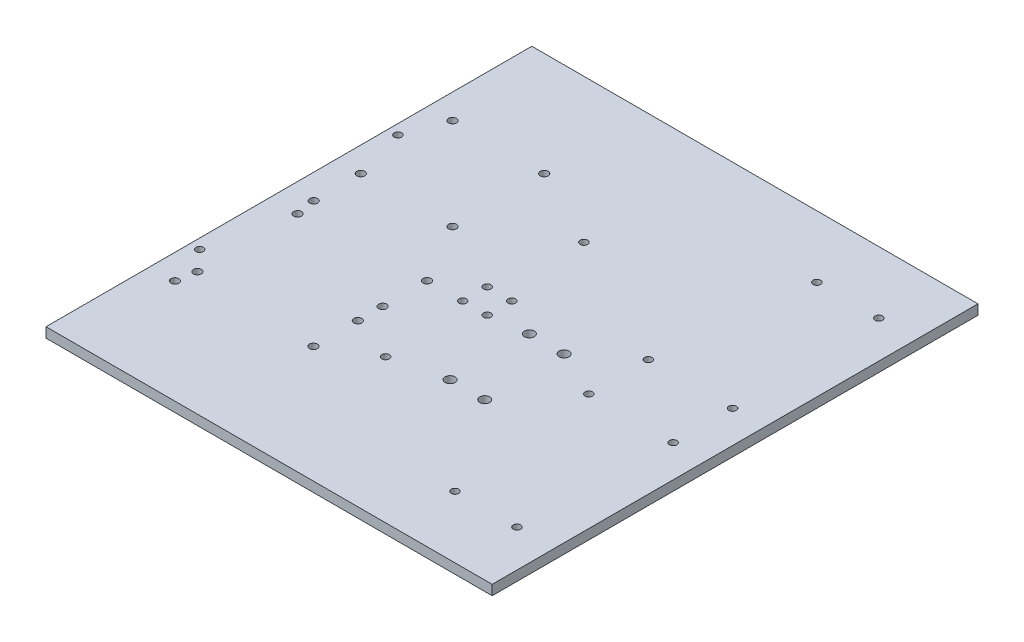
SolidWorks part; units mm, degrees
ref_plane "前视基准面" through (0, 0, 0) normal (0, 0, 1) x (1, 0, 0)
ref_plane "上视基准面" through (0, 0, 0) normal (0, 1, 0) x (1, 0, 0)
ref_plane "右视基准面" through (0, 0, 0) normal (1, 0, 0) x (0, 0, -1)
other "Configuration Table"
sketch "草图1" plane through (0, 0, 0) normal (0, 1, 0) x (1, 0, 0)
  line L1 (-90, -80) -> (90, -80)
  line L2 (-90, -80) -> (-90, 80)
  line L3 (-90, 80) -> (90, 80)
  line L4 (90, -80) -> (90, 80)
  line L5 (-90, -80) -> (90, 80) construction
  line L6 (-90, 80) -> (90, -80) construction
  point P0 (0, 0)
  dimension "D1" = 160
  dimension "D2" = 180
extrude "凸台-拉伸1" add sketch "草图1" along normal blind 4
sketch "草图2" plane through (0, 4, 0) normal (0, 1, 0) x (1, 0, 0)
  line L0 (90, -80) -> (90, 80) construction
  line L1 (66, -25) -> (85, -25) construction
  line L2 (66, -25) -> (66, 25) construction
  line L3 (66, 25) -> (85, 25) construction
  line L4 (85, -25) -> (85, 25) construction
  line L5 (66, -25) -> (85, 25) construction
  line L6 (66, 25) -> (85, -25) construction
  circle A0 centre (66, 25) radius 1.6
  circle A1 centre (66, -25) radius 1.6
  circle A2 centre (85, -25) radius 1.6
  circle A3 centre (85, 25) radius 1.6
  circle A7 centre (80.7, 7) radius 3
  point P0 (75.5, 0)
  dimension "D4" = 3.2
  dimension "D5" = 4.3
  dimension "D7" = 6
  dimension "D1" = 19
  dimension "D2" = 50
  dimension "D3" = 5
  dimension "D6" = 18
sketch "草图4" plane through (0, 4, 0) normal (0, 1, 0) x (1, 0, 0)
  line L0 (90, 80) -> (-90, 80) construction
  line L1 (-80, 56) -> (-43, 56) construction
  line L2 (-80, 56) -> (-80, 19) construction
  line L3 (-80, 19) -> (-43, 19) construction
  line L4 (-43, 56) -> (-43, 19) construction
  line L5 (-90, 80) -> (-90, -80) construction
  circle A0 centre (-80, 56) radius 1.6
  circle A1 centre (-43, 56) radius 1.6
  circle A2 centre (-43, 19) radius 1.6
  circle A3 centre (-80, 19) radius 1.6
  dimension "D4" = 3.2
  dimension "D1" = 37
  dimension "D2" = 24
  dimension "D3" = 10
extrude "切除-拉伸3" cut sketch "草图4" against normal blind 4
sketch "草图5" plane through (0, 4, 0) normal (0, 1, 0) x (1, 0, 0)
  line L0 (-90, -80) -> (90, -80) construction
  line L1 (-80, -56) -> (-29.2, -56) construction
  line L2 (-80, -56) -> (-80, -7.8) construction
  line L3 (-80, -7.8) -> (-29.2, -7.8) construction
  line L4 (-29.2, -56) -> (-29.2, -7.8) construction
  line L5 (-18.0867, -28) -> (49981.9133, -28) construction
  line L6 (-90, 80) -> (-90, -80) construction
  circle A0 centre (-78.7, -7.8) radius 1.6
  circle A1 centre (-29.2, -23) radius 1.6
  circle A2 centre (-29.2, -50.9) radius 1.6
  circle A3 centre (-80, -56) radius 1.6
  circle A4 centre (-29.2, -5.1) radius 1.6
  circle A5 centre (-29.2, -33) radius 1.6
  circle A6 centre (-80, 0) radius 1.6
  circle A7 centre (-78.7, -48.2) radius 1.6
  dimension "D8" = 3.2
  dimension "D1" = 48.2
  dimension "D2" = 50.8
  dimension "D3" = 24
  dimension "D4" = 10
  dimension "D5" = 1.3
  dimension "D6" = 15.2
  dimension "D7" = 27.9
  dimension "D9" = 52
extrude "切除-拉伸4" cut sketch "草图5" against normal blind 4
sketch "草图7" plane through (0, 0, 0) normal (0, -1, 0) x (1, 0, 0)
  line L0 (-90, 80) -> (90, 80) construction
  line L2 (90, 80) -> (90, -80) construction
  circle A0 centre (24, 35) radius 2
  circle A1 centre (10, 35) radius 2
  circle A2 centre (24, 3) radius 2
  circle A3 centre (10, 3) radius 2
  dimension "D2" = 4
  dimension "D5" = 4
  dimension "D1" = 80
  dimension "D3" = 45
  dimension "D6" = 14
  dimension "D7" = 32
extrude "切除-拉伸5" cut sketch "草图7" against normal blind 10
sketch "草图8" plane through (0, 0, 0) normal (0, -1, 0) x (1, 0, 0)
  line L1 (-14.9497, -4.9497) -> (-5.0503, -4.9497) construction
  line L2 (-14.9497, -4.9497) -> (-14.9497, 4.9497) construction
  line L3 (-14.9497, 4.9497) -> (-5.0503, 4.9497) construction
  line L4 (-5.0503, -4.9497) -> (-5.0503, 4.9497) construction
  line L5 (-14.9497, -4.9497) -> (-5.0503, 4.9497) construction
  line L6 (-14.9497, 4.9497) -> (-5.0503, -4.9497) construction
  circle A0 centre (-14.9497, 4.9497) radius 1.5
  circle A1 centre (-5.0503, 4.9497) radius 1.5
  circle A2 centre (-14.9497, -4.9497) radius 1.5
  circle A3 centre (-5.0503, -4.9497) radius 1.5
  point P0 (-10, 0)
  dimension "D4" = 3
  dimension "D1" = 14
  dimension "D3" = 10
extrude "切除-拉伸6" cut sketch "草图8" against normal blind 10
sketch "草图11" plane through (0, 0, 0) normal (0, -1, 0) x (1, 0, 0)
  line L0 (60, 80) -> (60, -80) construction
  line L1 (-90, 0) -> (90, 0) construction
  line L2 (90, 80) -> (90, -80) construction
  line L3 (-90, -80) -> (-90, 80) construction
  line L4 (90, -80) -> (-90, -80) construction
  line L5 (-90, 80) -> (90, 80) construction
  circle A0 centre (77, 12) radius 1.5
  circle A1 centre (43, 12) radius 1.5
  circle A2 centre (77, -12) radius 1.5
  circle A3 centre (43, -12) radius 1.5
  dimension "D1" = 3
  dimension "D2" = 24
  dimension "D3" = 34
  dimension "D4" = 30
extrude "切除-拉伸8" cut sketch "草图11" against normal blind 4
sketch "草图12" plane through (0, 0, 0) normal (0, -1, 0) x (1, 0, 0)
  line L0 (-90, -80) -> (-90, 80) construction
  line L1 (-11, -40) -> (-86, -40) construction
  line L2 (-11, -40) -> (-11, 40) construction
  line L3 (-11, 40) -> (-86, 40) construction
  line L4 (-86, -40) -> (-86, 40) construction
  line L5 (-11, -40) -> (-86, 40) construction
  line L6 (-11, 40) -> (-86, -40) construction
  circle A0 centre (-86, 40) radius 1.5
  circle A1 centre (-11, 40) radius 1.5
  circle A2 centre (-11, -40) radius 1.5
  circle A3 centre (-86, -40) radius 1.5
  point P0 (-48.5, 0)
  dimension "D4" = 3
  dimension "D1" = 4
  dimension "D2" = 75
  dimension "D3" = 80
extrude "切除-拉伸9" cut sketch "草图12" against normal blind 4
sketch "草图13" plane through (0, 0, -80) normal (0, 0, -1) x (-1, 0, 0)
  line L4 (-90, 0) -> (90, 0)
  line L5 (90, 0) -> (90, 4)
  line L6 (90, 4) -> (-90, 4)
  line L7 (-90, 4) -> (-90, 0)
  line L8 (-90, 0) -> (90, 0)
  line L9 (90, 0) -> (90, 4)
  line L10 (90, 4) -> (-90, 4)
  line L11 (-90, 4) -> (-90, 0)
  dimension "D1" = 0
extrude "凸台-拉伸2" add sketch "草图13" along normal blind 18
mirror "镜向1" about plane through (0, 0, 0) normal (0, 0, 1) of "凸台-拉伸2"
sketch "草图15" plane through (0, 4, 0) normal (0, 1, 0) x (1, 0, 0)
  line L0 (-90, -98) -> (90, -98) construction
  line L1 (90, -98) -> (90, 98) construction
  circle A0 centre (75, -73) radius 1.5
  circle A1 centre (50, -73) radius 1.5
  point P8 (0, 0)
  point P9 (0, 0)
  dimension "D2" = 3
  dimension "D5" = 3
  dimension "D1" = 25
  dimension "D3" = 15
  dimension "D4" = 25
extrude "切除-拉伸10" cut sketch "草图15" against normal through all
mirror "镜向2" about plane through (0, 0, 0) normal (0, 0, 1) of "切除-拉伸10"
